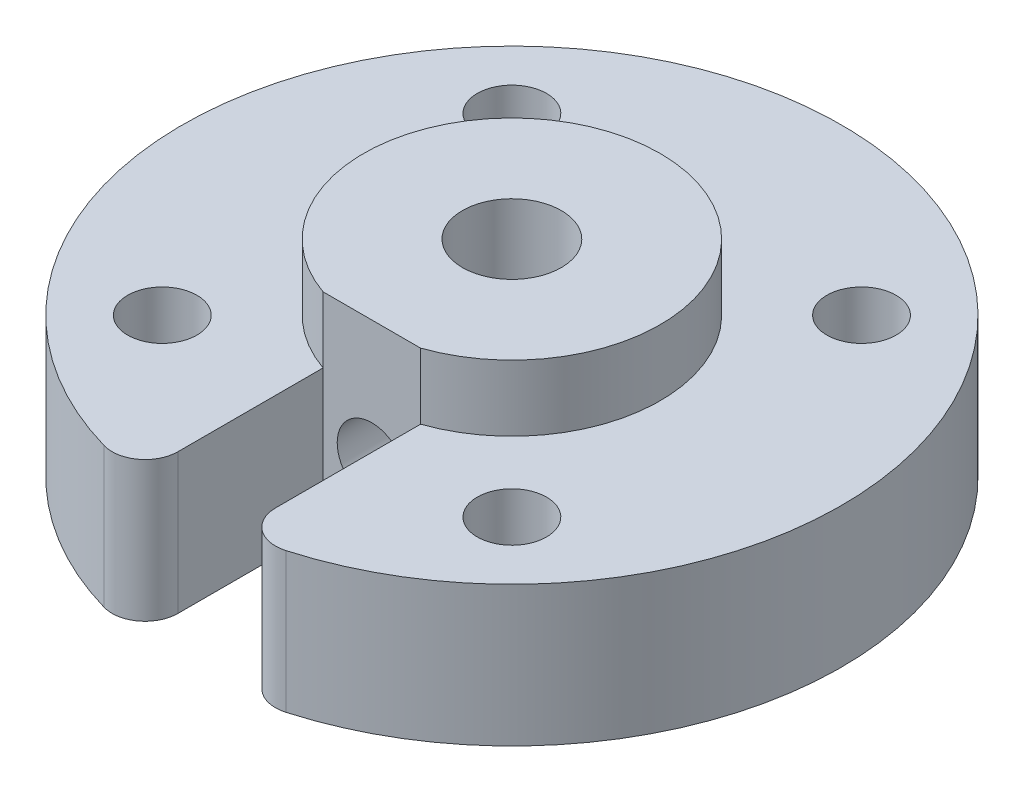
SolidWorks part; units mm, degrees
ref_plane "Front Plane" through (0, 0, 0) normal (0, 0, 1) x (1, 0, 0)
ref_plane "Top Plane" through (0, 0, 0) normal (0, 1, 0) x (1, 0, 0)
ref_plane "Right Plane" through (0, 0, 0) normal (1, 0, 0) x (0, 0, -1)
sketch "Sketch1" plane through (0, 0, 0) normal (0, 1, 0) x (1, 0, 0)
  circle A0 centre (0, 0) radius 9
  circle A1 centre (0, 0) radius 3
  dimension "D1" = 18
  dimension "D2" = 6
extrude "Boss-Extrude1" add sketch "Sketch1" along normal blind 12.5
hole_wizard "Ø4.2 (4.2) Diameter Hole1" positions "Sketch3" profile "Sketch5" hole size "Ø4.2" standard "DIN"
sketch "Sketch3" plane through (0, 0, 0) normal (0, 0, 1) x (1, 0, 0)
  line L2 (0, 0) -> (0, 5)
  line L3 (-9, 0) -> (9, 0) construction
  point P7 (0, 5)
  dimension "D1" = 5
sketch "Sketch5" plane through (0, 5, 0) normal (1, 0, 0) x (0, 1, 0)
  line L0 (0, 0) -> (0, 9)
  line L1 (0, 9) -> (2.1, 9)
  line L2 (2.1, 9) -> (2.1, 0)
  line L5 (2.1, 0) -> (0, 0)
  line L11 (0, -6.35) -> (0, 107.95) construction
  dimension "Thru Hole Dia." = 4.2
  dimension "Thru Hole Depth" = 9
sketch "Sketch6" plane through (0, 0, 0) normal (0, 0, 1) x (1, 0, 0)
  line L1 (-9, 12.5) -> (9, 12.5)
  line L2 (-9, 12.5) -> (-9, 0)
  line L3 (-9, 0) -> (9, 0)
  line L4 (9, 12.5) -> (9, 0)
extrude "Cut-Extrude1" cut sketch "Sketch6" against normal blind 0.5 from offset 9
sketch "Sketch7" plane through (0, 0, 0) normal (0, -1, 0) x (1, 0, 0)
  line L0 (-2.958, 8.5) -> (2.958, 8.5) construction
  line L1 (-2.958, 8.5) -> (2.958, 8.5)
  line L2 (-2.958, 8.5) -> (-2.958, 19.78)
  line L3 (2.958, 8.5) -> (2.958, 19.78)
  arc A0 (-2.958, 19.78) -> (2.958, 19.78) centre (0, 0) ccw
  arc A1 (-2.958, 8.5) -> (2.958, 8.5) centre (0, 0) ccw construction
  arc A2 (-2.958, 8.5) -> (2.958, 8.5) centre (0, 0) ccw
  arc M4 (-2.958, 8.5) -> (2.958, 8.5) centre (0, 0) ccw
  dimension "D1" = 40
extrude "Boss-Extrude2" add sketch "Sketch7" against normal blind 8.5 contours L2 A0 L3 M4
fillet "Fillet1" radius 2 2 edges at (-2.958, 4.25, 19.78) (2.958, 4.25, 19.78)
hole_wizard "Ø4.2 (4.2) Diameter Hole2" positions "Sketch8" profile "Sketch9" hole size "Ø4.2" standard "DIN" end condition through all
sketch "Sketch8" plane through (0, 0, 0) normal (0, -1, 0) x (-1, 0, 0)
  line L0 (0, 0) -> (-10.6066, -10.6066) construction
  circle A0 centre (0, 0) radius 15 construction
  point P7 (-10.6066, -10.6066)
  point P16 (-10.6066, 10.6066)
  point P17 (10.6066, 10.6066)
  point P18 (10.6066, -10.6066)
  dimension "D1" = 30
  dimension "D2" = 4
sketch "Sketch9" plane through (-10.6066, 0, 10.6066) normal (1, 0, 0) x (0, 0, -1)
  line L0 (0, 0) -> (0, 12.5)
  line L1 (0, 12.5) -> (2.1, 12.5)
  line L2 (2.1, 12.5) -> (2.1, 0)
  line L5 (2.1, 0) -> (0, 0)
  line L11 (0, -6.35) -> (0, 107.95) construction
  dimension "Thru Hole Dia." = 4.2
  dimension "Thru Hole Depth" = 12.5
